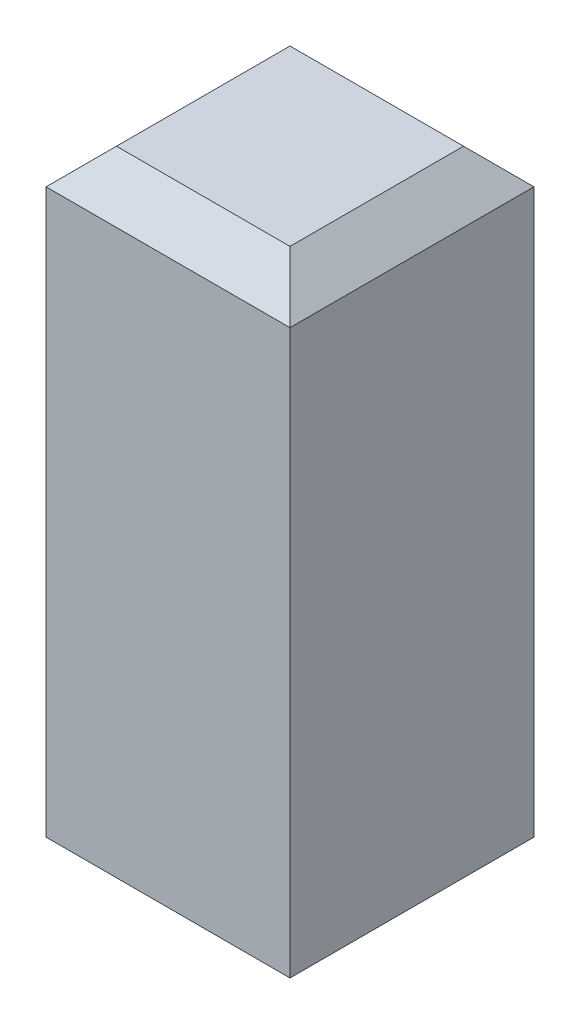
SolidWorks part; units mm, degrees
ref_plane "Front Plane" through (0, 0, 0) normal (0, 0, 1) x (1, 0, 0)
ref_plane "Top Plane" through (0, 0, 0) normal (0, 1, 0) x (1, 0, 0)
ref_plane "Right Plane" through (0, 0, 0) normal (1, 0, 0) x (0, 0, -1)
sketch "Sketch1" plane through (0, 0, 0) normal (0, 1, 0) x (1, 0, 0)
  line L5 (0, 0) -> (4.4003, 0)
  line L6 (0, 0) -> (0, 4.4003)
  line L7 (0, 4.4003) -> (4.4003, 4.4003)
  line L8 (4.4003, 0) -> (4.4003, 4.4003)
  dimension "D1" = 6.223
extrude "Boss-Extrude1" add sketch "Sketch1" along normal blind 11.43
chamfer "Chamfer1" distance 0.635 angle 45 8 edges at (2.2002, 0, 0) (4.4003, 0, -2.2002) (2.2002, 0, -4.4003) (0, 0, -2.2002) (2.2002, 11.43, -4.4003) (4.4003, 11.43, -2.2002) (2.2002, 11.43, 0) (0, 11.43, -2.2002)
